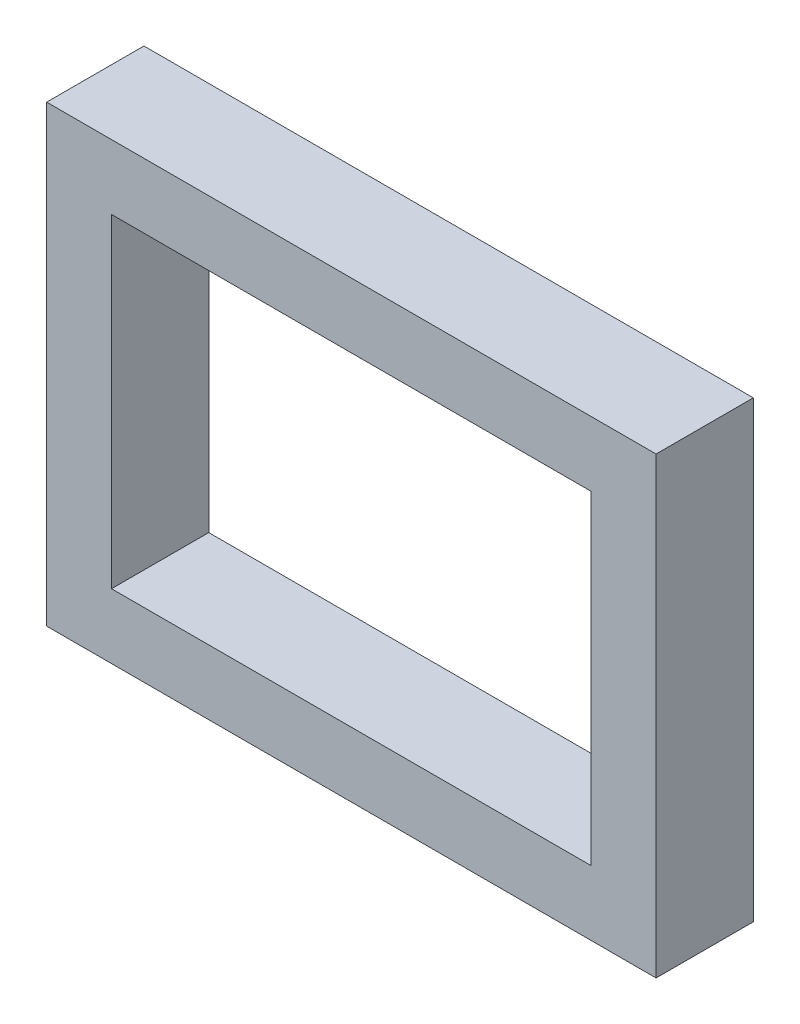
SolidWorks part; units mm, degrees
ref_plane "Front Plane" through (0, 0, 0) normal (0, 0, 1) x (1, 0, 0)
ref_plane "Top Plane" through (0, 0, 0) normal (0, 1, 0) x (1, 0, 0)
ref_plane "Right Plane" through (0, 0, 0) normal (1, 0, 0) x (0, 0, -1)
sketch "Sketch1" plane through (0, 0, 0) normal (0, 0, 1) x (1, 0, 0)
  line L0 (-23.495, 15.875) -> (23.495, 15.875)
  line L9 (-29.845, 22.225) -> (29.845, 22.225)
  line L10 (-29.845, 22.225) -> (-29.845, -22.225)
  line L11 (-29.845, -22.225) -> (29.845, -22.225)
  line L12 (29.845, 22.225) -> (29.845, -22.225)
  line L13 (-29.845, 22.225) -> (29.845, -22.225) construction
  line L14 (-29.845, -22.225) -> (29.845, 22.225) construction
  line L19 (-7.393, 5.5055) -> (21.5985, -16.084) construction
  line L20 (-14.9755, -10.1186) -> (14.9755, 10.1186) construction
  line L21 (23.495, 15.875) -> (23.495, -15.875)
  line L22 (-23.495, -15.875) -> (23.495, -15.875)
  line L23 (-23.495, 15.875) -> (-23.495, -15.875)
  point P0 (0, 0)
  point P6 (0, 0)
  dimension "D1" = 59.69
  dimension "D2" = 44.45
  dimension "D3" = 6.35
extrude "Boss-Extrude1" add sketch "Sketch1" along normal blind 9.525
